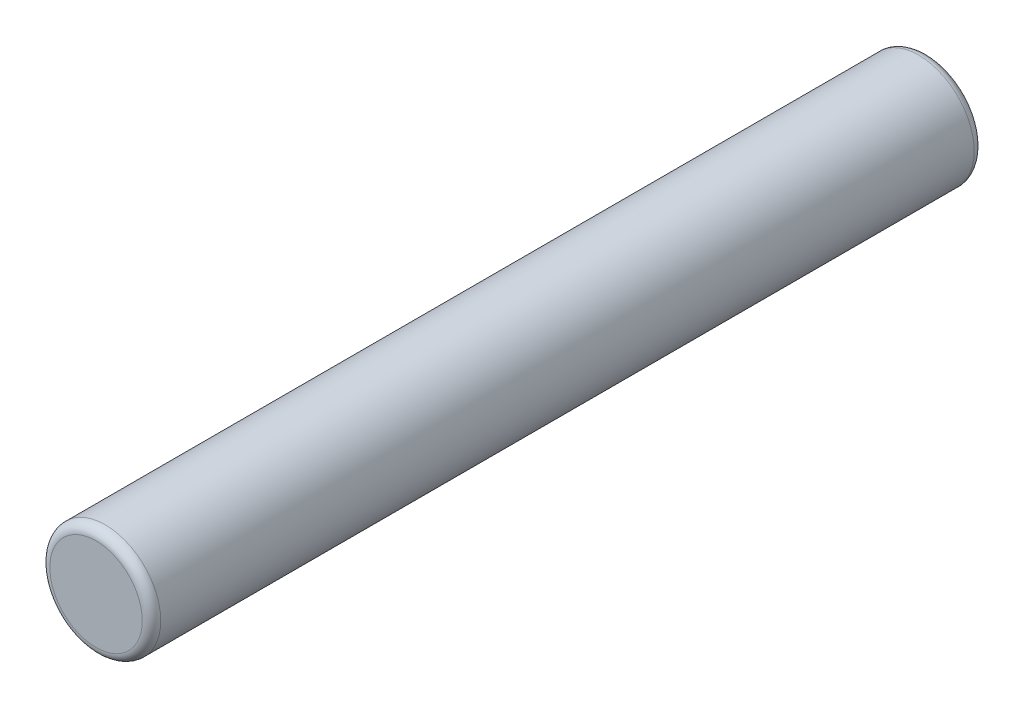
SolidWorks part; units mm, degrees
ref_plane "Front Plane" through (0, 0, 0) normal (0, 0, 1) x (1, 0, 0)
ref_plane "Top Plane" through (0, 0, 0) normal (0, 1, 0) x (1, 0, 0)
ref_plane "Right Plane" through (0, 0, 0) normal (1, 0, 0) x (0, 0, -1)
sketch "Sketch1" plane through (0, 0, 0) normal (0, 0, 1) x (1, 0, 0)
  circle A0 centre (0, 0) radius 3
extrude "Boss-Extrude1" add sketch "Sketch1" along normal mid plane 45
fillet "Fillet1" radius 0.5 2 edges at (3, 0, -22.5) (3, 0, 22.5)
